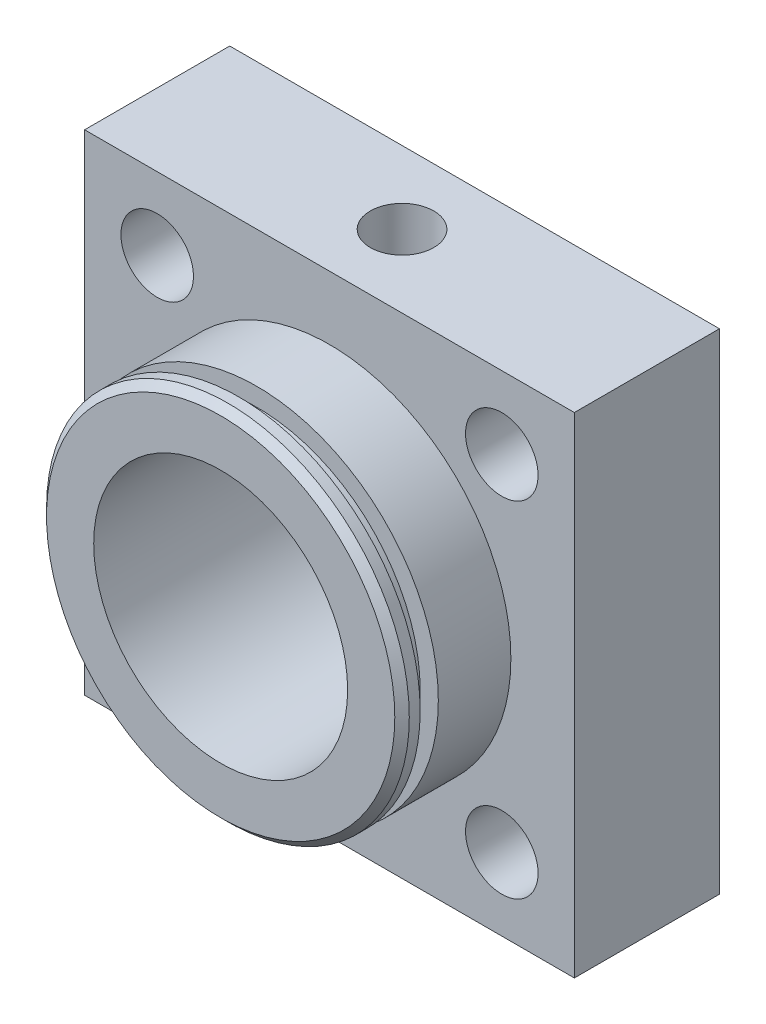
SolidWorks part; units mm, degrees
ref_plane "Front Plane" through (0, 0, 0) normal (0, 0, 1) x (1, 0, 0)
ref_plane "Top Plane" through (0, 0, 0) normal (0, 1, 0) x (1, 0, 0)
ref_plane "Right Plane" through (0, 0, 0) normal (1, 0, 0) x (0, 0, -1)
sketch "Sketch1" plane through (0, 0, 0) normal (0, 0, 1) x (1, 0, 0)
  line L1 (67.5, -67.5) -> (-67.5, -67.5)
  line L2 (67.5, -67.5) -> (67.5, 67.5)
  line L3 (67.5, 67.5) -> (-67.5, 67.5)
  line L4 (-67.5, -67.5) -> (-67.5, 67.5)
  line L5 (67.5, -67.5) -> (-67.5, 67.5) construction
  line L6 (67.5, 67.5) -> (-67.5, -67.5) construction
  point P0 (0, 0)
  dimension "D1" = 135
  dimension "D2" = 135
extrude "Boss-Extrude1" add sketch "Sketch1" along normal blind 40
sketch "Sketch2" plane through (0, 0, 40) normal (0, 0, 1) x (1, 0, 0)
  line L0 (0, 69.3225) -> (0, -73.1884) construction
  line L1 (-76.4392, 0) -> (76.4392, 0) construction
  line L2 (67.5, 67.5) -> (-67.5, 67.5) construction
  line L3 (-67.5, 67.5) -> (-67.5, -67.5) construction
  circle A0 centre (-47.5, 47.5) radius 10
  circle A1 centre (47.5, 47.5) radius 10
  circle A2 centre (47.5, -47.5) radius 10
  circle A3 centre (-47.5, -47.5) radius 10
  point P8 (0, 0)
  dimension "D1" = 20
  dimension "D2" = 20
  dimension "D3" = 20
extrude "Cut-Extrude1" cut sketch "Sketch2" against normal through all
sketch "Sketch4" plane through (0, 0, 40) normal (0, 0, 1) x (1, 0, 0)
  circle A0 centre (0, 0) radius 50
  dimension "D1" = 100
extrude "Boss-Extrude2" add sketch "Sketch4" along normal blind 20
sketch "Sketch5" plane through (0, 0, 60) normal (0, 0, 1) x (1, 0, 0)
  circle A0 centre (0, 0) radius 45
  dimension "D1" = 90
extrude "Boss-Extrude3" add sketch "Sketch5" along normal blind 5
sketch "Sketch6" plane through (0, 0, 65) normal (0, 0, 1) x (1, 0, 0)
  circle A0 centre (0, 0) radius 50
extrude "Boss-Extrude4" add sketch "Sketch6" along normal blind 5
chamfer "Chamfer1" distance 2 angle 45 1 edges at (50, 0, 70)
sketch "Sketch7" plane through (0, 0, 70) normal (0, 0, 1) x (1, 0, 0)
  circle A0 centre (0, 0) radius 35
  dimension "D1" = 70
extrude "Cut-Extrude2" cut sketch "Sketch7" against normal blind 65
sketch "Sketch8" plane through (0, -67.5, 0) normal (0, -1, 0) x (1, 0, 0)
  line L1 (-67.5, 40) -> (67.5, 40) construction
  line L2 (-67.5, 40) -> (-67.5, 0) construction
  line L3 (-67.5, 0) -> (67.5, 0) construction
  line L4 (67.5, 40) -> (67.5, 0) construction
  line L5 (-67.5, 40) -> (67.5, 0) construction
  line L6 (-67.5, 0) -> (67.5, 40) construction
  circle A0 centre (0, 20) radius 10
  point P4 (0, 20)
  dimension "D1" = 20
hole_wizard "M20x2.5 Tapped Hole1" positions "3DSketch1" profile "Sketch9" tap size "M20x2.5" standard "ANSI Metric" end condition through all
sketch3d "3DSketch1"
  point P0 (0, -67.5, 20)
sketch "Sketch9" plane through (0, -67.5, 20) normal (1, 0, 0) x (0, 0, -1)
  line L0 (0, 0) -> (0, 135)
  line L1 (0, 135) -> (8.75, 135)
  line L2 (8.75, 135) -> (8.75, 0)
  line L5 (8.75, 0) -> (0, 0)
  line L11 (0, -6.35) -> (0, 107.95) construction
  dimension "Thru Tap Drill Dia." = 17.5
  dimension "Thru Tap Drill Depth" = 135
cosmetic thread "Hole Thread1" parameters "D2"=20
ref_plane "Plane1" through (0, 0, 0) normal (-1, 0, 0) x (0, 0, 1)
